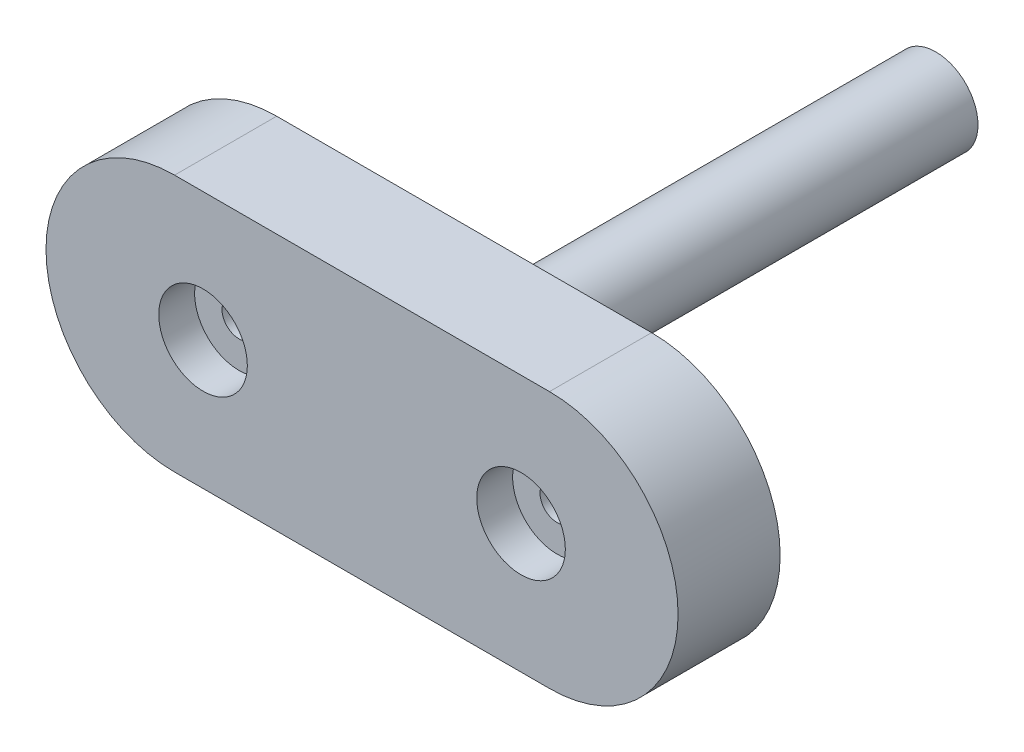
SolidWorks part; units mm, degrees
ref_plane "Alzado" through (0, 0, 0) normal (0, 0, 1) x (1, 0, 0)
ref_plane "Planta" through (0, 0, 0) normal (0, 1, 0) x (1, 0, 0)
ref_plane "Vista lateral" through (0, 0, 0) normal (1, 0, 0) x (0, 0, -1)
sketch "Croquis1" plane through (0, 0, 0) normal (0, 0, 1) x (1, 0, 0)
  line L0 (-17.685, 0) -> (17.685, 0) construction
  line L1 (-17.685, 12.13) -> (17.685, 12.13)
  line L2 (-17.685, -12.13) -> (17.685, -12.13)
  arc A0 (-17.685, 12.13) -> (-17.685, -12.13) centre (-17.685, 0) ccw
  arc A1 (17.685, -12.13) -> (17.685, 12.13) centre (17.685, 0) ccw
  point P2 (0, 0)
  point P7 (0, 0)
  point P8 (-29.815, 0)
  point P10 (29.815, 0)
  dimension "D1" = 59.63
  dimension "D2" = 12.13
extrude "Saliente-Extruir1" add sketch "Croquis1" against normal blind 9.63
sketch "Croquis2" plane through (0, 0, -9.63) normal (0, 0, -1) x (-1, 0, 0)
  circle A0 centre (0, 0) radius 3.98
  dimension "D1" = 7.96
extrude "Saliente-Extruir2" add sketch "Croquis2" along normal blind 44.5
sketch "Croquis3" plane through (0, 0, 0) normal (0, 0, 1) x (1, 0, 0)
  line L0 (-15, 0) -> (15, 0)
  circle A0 centre (-15, 0) radius 1.6
  circle A1 centre (15, 0) radius 1.6
  point P0 (15, -0.0896)
  point P4 (-15, -0.0727)
  point P9 (0, 0)
  dimension "D1" = 3.2
  dimension "D2" = 30
extrude "Cortar-Extruir1" cut sketch "Croquis3" against normal through all
sketch "Croquis4" plane through (0, 0, 0) normal (0, 0, 1) x (1, 0, 0)
  circle A0 centre (-15, 0) radius 4.18
  circle A1 centre (15, 0) radius 4.18
  dimension "D1" = 8.36
extrude "Cortar-Extruir2" cut sketch "Croquis4" against normal blind 3.39
